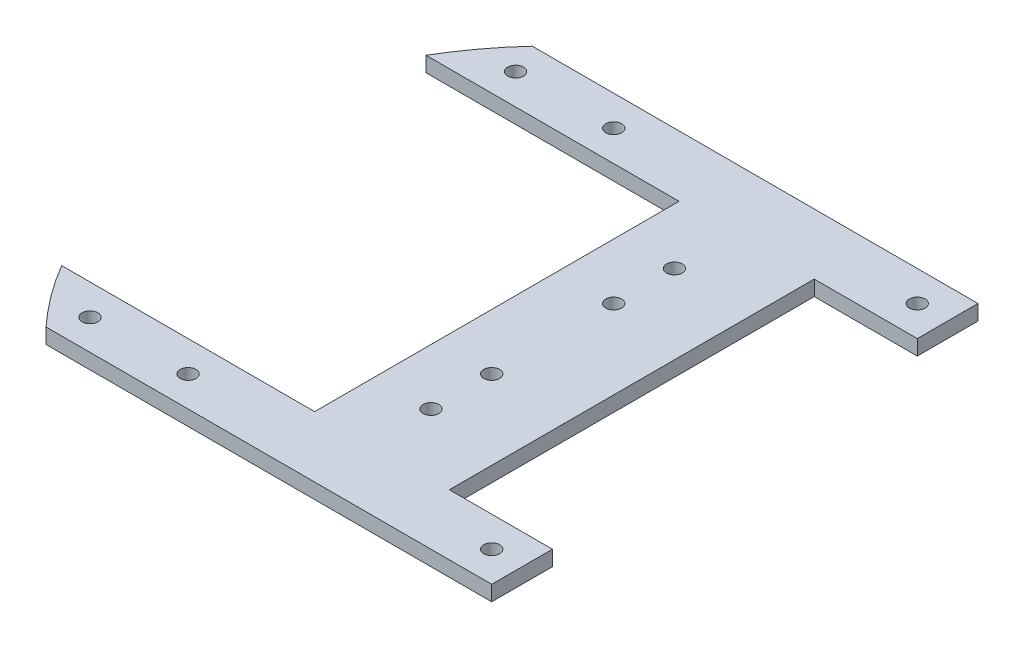
SolidWorks part; units mm, degrees
ref_plane "Front Plane" through (0, 0, 0) normal (0, 0, 1) x (1, 0, 0)
ref_plane "Top Plane" through (0, 0, 0) normal (0, 1, 0) x (1, 0, 0)
ref_plane "Right Plane" through (0, 0, 0) normal (1, 0, 0) x (0, 0, -1)
sketch "Sketch1" plane through (0, 0, 0) normal (0, 1, 0) x (1, 0, 0)
  line L0 (-73.9169, 12.7) -> (-73.9169, -12.7)
  line L1 (55.1228, -50.8575) -> (-55.1228, -50.8575)
  line L2 (-55.1228, 50.8575) -> (55.1228, 50.8575)
  line L3 (29.2721, -56.6995) -> (-29.2721, -56.6995) construction
  line L5 (47.9323, 0) -> (-73.9169, 0) construction
  arc A0 (-73.9169, -12.7) -> (-55.1228, -50.8575) centre (0, 0) ccw
  arc A1 (-55.1228, 50.8575) -> (-73.9169, 12.7) centre (0, 0) ccw
  arc A2 (55.1228, -50.8575) -> (67.2709, -33.1606) centre (0, 0) ccw
  arc A3 (67.2709, 33.1606) -> (67.2709, -33.1606) centre (86.0323, 0) ccw
  arc A4 (67.2709, 33.1606) -> (55.1228, 50.8575) centre (0, 0) ccw
  arc A5 (50.3421, -13.335) -> (67.2709, -33.1606) centre (86.0323, 0) ccw construction
  circle A6 centre (0, -12.7575) radius 1.651
  circle A7 centre (0, -25.4575) radius 1.651
  circle A8 centre (31.75, -44.5075) radius 1.651
  circle A9 centre (-31.75, -44.5075) radius 1.651
  circle A10 centre (-52.2677, 44.5075) radius 1.651
  circle A11 centre (-52.2677, -44.5075) radius 1.651
  circle A12 centre (-31.75, 44.5075) radius 1.651
  circle A13 centre (31.75, 44.5075) radius 1.651
  circle A14 centre (0, 25.4575) radius 1.651
  circle A15 centre (0, 12.7575) radius 1.651
  circle A16 centre (31.75, -44.5075) radius 1.651 construction
  dimension "D1" = 150
  dimension "D2" = 25.4
  dimension "D3" = 5.842
extrude "Boss-Extrude1" add sketch "Sketch1" along normal blind 3.175
sketch "Sketch2" plane through (0, 3.175, 0) normal (0, 1, 0) x (1, 0, 0)
  line L0 (38.1, -50.8575) -> (38.1, -38.1575)
  line L1 (-55.1228, -50.8575) -> (55.1228, -50.8575) construction
  line L2 (38.1, -38.1575) -> (16.5505, -38.1575)
  line L3 (16.5505, -38.1575) -> (16.5505, 38.1575)
  line L4 (16.5505, 38.1575) -> (38.1, 38.1575)
  line L5 (38.1, 38.1575) -> (38.1, 50.8575)
  line L6 (55.1228, 50.8575) -> (-55.1228, 50.8575) construction
  line L7 (38.1, 50.8575) -> (55.1228, 50.8575)
  line L8 (38.1, -50.8575) -> (55.1228, -50.8575)
  line L10 (-64.6018, 38.1) -> (-11.6869, 38.1)
  line L11 (-11.6869, 38.1) -> (-11.6869, -38.1)
  line L12 (-11.6869, -38.1) -> (-64.6018, -38.1)
  line L13 (-73.9169, 12.7) -> (-73.9169, -12.7)
  line L14 (10.2005, 8.5575) -> (10.2005, 33.6575) construction
  arc A0 (55.1228, -50.8575) -> (67.2709, -33.1606) centre (0, 0) ccw
  arc A1 (55.1228, -50.8575) -> (67.2709, -33.1606) centre (0, 0) ccw construction
  arc A2 (55.1228, 50.8575) -> (67.2709, 33.1606) centre (0, 0) cw
  arc A3 (67.2709, 33.1606) -> (55.1228, 50.8575) centre (0, 0) ccw construction
  arc A4 (67.2709, 33.1606) -> (67.2709, -33.1606) centre (86.0323, 0) ccw
  arc A5 (67.2709, 33.1606) -> (67.2709, -33.1606) centre (86.0323, 0) ccw construction
  circle A6 centre (31.75, 44.5075) radius 1.651 construction
  arc A7 (-55.1228, 50.8575) -> (-73.9169, 12.7) centre (0, 0) ccw construction
  arc A8 (-73.9169, -12.7) -> (-55.1228, -50.8575) centre (0, 0) ccw construction
  arc A9 (-64.6018, 38.1) -> (-73.9169, 12.7) centre (0, 0) ccw
  arc A10 (67.2709, 33.1606) -> (-73.9169, 12.7) centre (0, 0) ccw construction
  arc A11 (-73.9169, -12.7) -> (-64.6018, -38.1) centre (0, 0) ccw
  circle A13 centre (-15.4969, -34.29) radius 1.651 construction
  dimension "D1" = 6.35
  dimension "D3" = 6.35
  dimension "D5" = 76.2
  dimension "D2" = 6.35
  dimension "D4" = 3.81
extrude "Cut-Extrude1" cut sketch "Sketch2" against normal up to surface (3.175 mm away) up to face at (0, 0, -27.1085)
